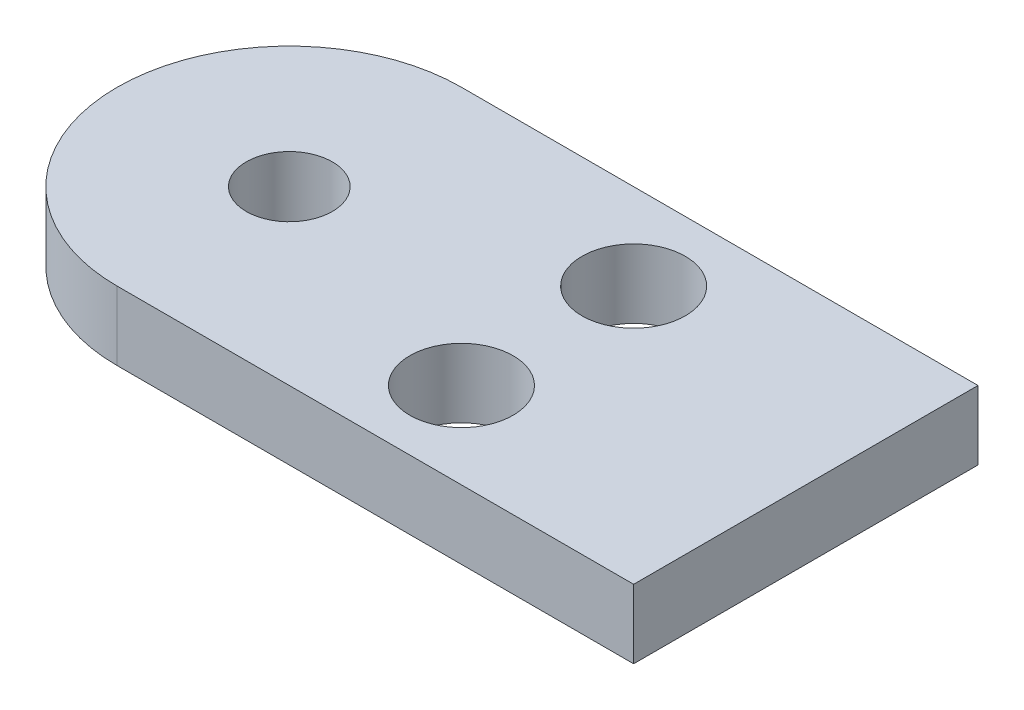
SolidWorks part; units mm, degrees
ref_plane "Front Plane" through (0, 0, 0) normal (0, 0, 1) x (1, 0, 0)
ref_plane "Top Plane" through (0, 0, 0) normal (0, 1, 0) x (1, 0, 0)
ref_plane "Right Plane" through (0, 0, 0) normal (1, 0, 0) x (0, 0, -1)
sketch "Sketch1" plane through (0, 0, 0) normal (0, 1, 0) x (1, 0, 0)
  line L0 (0, 0) -> (10, 0) construction
  line L2 (10, 10) -> (30, 10)
  line L3 (30, 10) -> (30, -10)
  line L4 (30, -10) -> (10, -10)
  line L5 (0, 10) -> (10, 10)
  line L6 (0, -10) -> (10, -10)
  circle A0 centre (0, 0) radius 2.5
  arc A1 (0, 10) -> (0, -10) centre (0, 0) ccw
  point P7 (10, 0)
  dimension "D1" = 10
  dimension "D2" = 5
extrude "Boss-Extrude1" add sketch "Sketch1" along normal blind 4
sketch "Sketch2" plane through (0, 4, 0) normal (0, 1, 0) x (1, 0, 0)
  line L0 (10, 10) -> (10, -10)
  line L1 (30, 10) -> (0, 10) construction
  line L2 (0, -10) -> (30, -10) construction
  line L3 (30, -10) -> (30, 10) construction
  line L4 (10, 10) -> (30, 10)
  line L5 (30, 10) -> (30, -10)
  line L6 (30, -10) -> (10, -10)
  dimension "D1" = 20
extrude "Boss-Extrude2" [suppressed] add sketch "Sketch2" along normal blind 10
sketch "Sketch3" [suppressed] plane through (0, 14, 0) normal (0, 1, 0) x (1, 0, 0)
  line L0 (10, 10) -> (30, -10) construction
  line L1 (10, -10) -> (30, 10) construction
  line L2 (20, 10) -> (20, -10) construction
  line L3 (30, 10) -> (10, 10) construction
  line L4 (10, -10) -> (30, -10) construction
  line L5 (20, -10) -> (10, 0) construction
  line L6 (10, 10) -> (10, -10) construction
  line L7 (10, 0) -> (20, 10) construction
  line L8 (20, 10) -> (30, 0) construction
  line L9 (30, -10) -> (30, 10) construction
  line L10 (30, 0) -> (20, -10) construction
  circle A0 centre (25, 5) radius 3
  circle A1 centre (25, -5) radius 3
extrude "Boss-Extrude3" [suppressed] add sketch "Sketch3" along normal blind 3
fillet "Fillet1" [suppressed] radius 2.5
sketch "Sketch4" [suppressed] plane through (0, 14, 0) normal (0, 1, 0) x (1, 0, 0)
  line L0 (10, 0) -> (20, 10) construction
  line L1 (20, -10) -> (10, 0) construction
  circle A0 centre (15, 5) radius 3
  circle A1 centre (15, -5) radius 3
extrude "Cut-Extrude1" [suppressed] cut sketch "Sketch4" against normal blind 3.5
sketch "Sketch5" plane through (0, 0, 0) normal (0, -1, 0) x (1, 0, 0)
  line L0 (0, 0) -> (-5.5, 0) construction
  line L1 (0, 0) -> (6.5, 0) construction
  line L2 (-5.5, -2.5) -> (-5.5, 2.5)
  line L3 (6.5, -5.5) -> (6.5, 5.5)
  line L4 (6.5, 5.5) -> (-2.5, 5.5)
  line L5 (-2.5, 5.5) -> (-5.5, 2.5)
  line L6 (6.5, -5.5) -> (-2.5, -5.5)
  line L7 (-2.5, -5.5) -> (-5.5, -2.5)
  point P7 (-5.5, 0)
  point P10 (6.5, 0)
  dimension "D1" = 6.5
  dimension "D2" = 5
  dimension "D3" = 11
  dimension "D4" = 5.5
extrude "Cut-Extrude2" cut sketch "Sketch5" against normal blind 0.2
sketch "Sketch6" plane through (0, 0, 0) normal (0, -1, 0) x (1, 0, 0)
  line L0 (5.5, -4.25) -> (5.5, 4.25) construction
  line L1 (0, 0) -> (10, 0) construction
  circle A0 centre (5.5, 4.25) radius 0.5
  circle A1 centre (5.5, -4.25) radius 0.5
  point P3 (5.5, 0)
  dimension "D3" = 1
  dimension "D1" = 8.5
  dimension "D2" = 5.5
extrude "Cut-Extrude3" cut sketch "Sketch6" against normal blind 1.5
sketch "Sketch7" plane through (0, 4, 0) normal (0, 1, 0) x (1, 0, 0)
  line L0 (30, -10) -> (10, 10) construction
  line L1 (10, 10) -> (10, -10) construction
  line L2 (10, -10) -> (30, 10) construction
  line L3 (30, 10) -> (20, 10) construction
  line L4 (10, 10) -> (30, 10) construction
  line L5 (20, 10) -> (20, -10) construction
  line L6 (30, -10) -> (10, -10) construction
  line L7 (20, -10) -> (10, 0) construction
  line L8 (10, 0) -> (20, 10) construction
  line L9 (30, 0) -> (20, 10) construction
  line L10 (30, 10) -> (30, -10) construction
  line L11 (30, 0) -> (20, -10) construction
  circle A0 centre (15, 5) radius 3
  circle A1 centre (15, -5) radius 3
extrude "Cut-Extrude4" cut sketch "Sketch7" against normal through all
